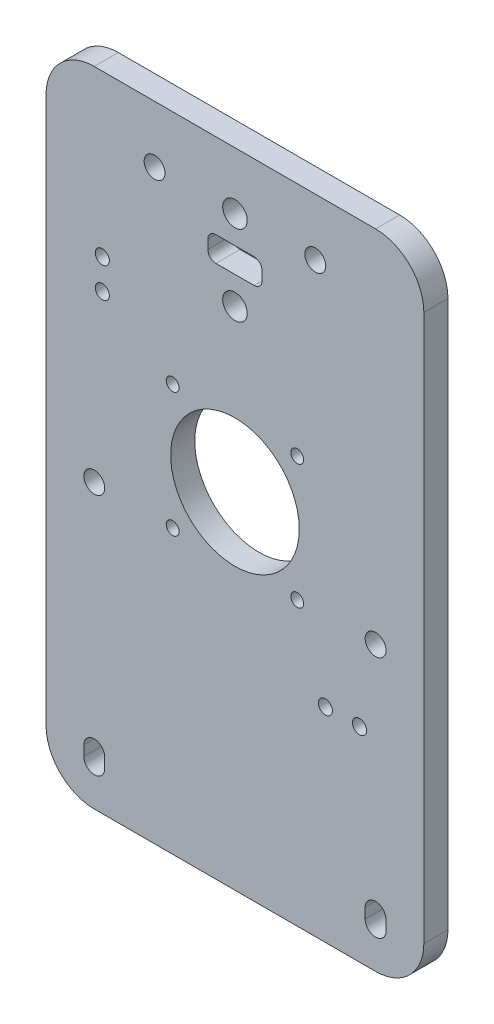
SolidWorks part; units mm, degrees
material "Acrylic (Medium-high impact)"
ref_plane "Спереди" through (0, 0, 0) normal (0, 0, 1) x (1, 0, 0)
ref_plane "Сверху" through (0, 0, 0) normal (0, 1, 0) x (1, 0, 0)
ref_plane "Справа" through (0, 0, 0) normal (1, 0, 0) x (0, 0, -1)
sketch "Model" plane through (0, 0, 0) normal (0, 0, 1) x (1, 0, 0)
  line L0 (-2.3021, 85.8) -> (5.2264, 85.8) construction
  line L1 (6.75, 135.8) -> (-6.75, 135.8) construction
  line L5 (0, 27.6115) -> (0, 21.6925) construction
  line L7 (-15.5, 9.9369) -> (-15.5, 9.0934) construction
  line L8 (15.5, 9.9369) -> (15.5, 9.0934) construction
  line L24 (-35, 37.2847) -> (-35, 77.3985) construction
  line L25 (-31.4983, 12.5) -> (-38.4, 12.5) construction
  line L26 (-31.4983, 10) -> (-38.4, 10) construction
  line L27 (-35, 12.5) -> (-35, 10) construction
  line L28 (-32.4, 12.5) -> (-32.4, 10)
  line L29 (-37.6, 12.5) -> (-37.6, 10)
  line L40 (31.4983, 10) -> (38.4, 10) construction
  line L41 (31.4983, 12.5) -> (38.4, 12.5) construction
  line L42 (35, 37.2847) -> (35, 77.3985) construction
  line L43 (35, 12.5) -> (35, 10) construction
  line L44 (32.4, 12.5) -> (32.4, 10)
  line L45 (37.6, 12.5) -> (37.6, 10)
  line L47 (-26.0102, 145.8) -> (26.0946, 145.8) construction
  line L48 (0, 129.408) -> (0, 90.7064) construction
  line L51 (-38.85, 70.45) -> (-29.8907, 70.45) construction
  line L53 (-16.3166, 125.8) -> (17.7871, 125.8) construction
  line L58 (38.85, 70.45) -> (29.8907, 70.45) construction
  line L4875 (-35, 160) -> (35, 160)
  line L4882 (47, 148) -> (47, 12)
  line L4889 (35, 0) -> (-35, 0)
  line L4896 (-47, 12) -> (-47, 148)
  line L5609 (6.75, 138.9) -> (-6.75, 138.9)
  line L5610 (-6.75, 138.9) -> (-6.75, 132.7)
  line L5611 (-6.75, 132.7) -> (6.75, 132.7)
  line L5612 (6.75, 132.7) -> (6.75, 138.9)
  line L6648 (-6.75, 138.9) -> (6.75, 138.9)
  line L6649 (6.75, 138.9) -> (6.75, 132.7)
  line L6650 (6.75, 132.7) -> (-6.75, 132.7)
  line L6651 (-6.75, 132.7) -> (-6.75, 138.9)
  arc A0 (-47, 12) -> (-35, 0) centre (-35, 12) ccw
  arc A1 (35, 0) -> (47, 12) centre (35, 12) ccw
  arc A2 (47, 148) -> (35, 160) centre (35, 148) ccw
  arc A3 (-35, 160) -> (-47, 148) centre (-35, 148) ccw
  circle A4 centre (0, 85.8) radius 16
  arc A13 (-32.4, 12.5) -> (-37.6, 12.5) centre (-35, 12.5) ccw
  arc A14 (-37.6, 10) -> (-32.4, 10) centre (-35, 10) ccw
  arc A19 (32.4, 12.5) -> (37.6, 12.5) centre (35, 12.5) cw
  arc A20 (37.6, 10) -> (32.4, 10) centre (35, 10) cw
  circle A29 centre (0, 145.8) radius 3.05
  circle A30 centre (-20, 145.8) radius 2.6
  circle A31 centre (20, 145.8) radius 2.6
  circle A32 centre (-35, 70.45) radius 2.6
  circle A33 centre (0, 125.8) radius 3.05
  circle A36 centre (35, 70.45) radius 2.6
  point P17 (0, 0)
  point P77 (-35, 11.25)
  point P114 (35, 11.25)
  point P127 (0, 160)
  dimension "D5" = 32
  dimension "D30" = 5.2
  dimension "D33" = 5.2
  dimension "D35" = 6.1
  dimension "D2" = 70
  dimension "D3" = 160
  dimension "D6" = 15.5
  dimension "D15" = 12
  dimension "D16" = 2.5
  dimension "D17" = 10
  dimension "D18" = 5.2
  dimension "D25" = 14.2
  dimension "D34" = 20
  dimension "D41" = 13.5
  dimension "D42" = 6.2
  dimension "D9" = 70
  dimension "D10" = 57.95
  dimension "D12" = 20
  dimension "D13" = 20
  dimension "D11" = 10
  dimension "D7" = 74.2
extrude "Base" add sketch "Model" along normal blind 6
sketch "Sketch1" plane through (0, 0, 6) normal (0, 0, 1) x (1, 0, 0)
  line L1 (-35, 160) -> (35, 160) construction
  line L2 (-47, 12) -> (-47, 148) construction
  circle A0 centre (-33, 120) radius 1.75
  circle A1 centre (-33, 112.5) radius 1.75
  dimension "D1" = 3.5
  dimension "D3" = 7.5
  dimension "D4" = 14
  dimension "D5" = 40
extrude "SensorMount" cut sketch "Sketch1" against normal through all contours A1 | A0
sketch "Sketch2" plane through (0, 0, 6) normal (0, 0, 1) x (1, 0, 0)
  line L0 (35, 0) -> (-35, 0) construction
  line L1 (-47, 12) -> (-47, 148) construction
  circle A0 centre (22.5, 50.76) radius 1.75
  circle A1 centre (31, 50.76) radius 1.75
  dimension "D1" = 3.5
  dimension "D3" = 8.5
  dimension "D4" = 50.76
  dimension "D5" = 69.5
extrude "CableMount" cut sketch "Sketch2" against normal blind 10 contours A0 | A1
fillet "FilletCableSlot" radius 2 4 edges at (6.75, 138.9, 3) (-6.75, 138.9, 3) (-6.75, 132.7, 3) (6.75, 132.7, 3)
hole_wizard "Ø3.2 (3.2) Stepper mount Holes" positions "Sketch6" profile "Sketch7" hole size "Ø3.2" standard "ANSI Metric" end condition through all
sketch "Sketch6" plane through (0, 0, 6) normal (0, 0, 1) x (1, 0, 0)
  line L0 (-50.1491, 85.8) -> (50.1491, 85.8) construction
  line L2 (0, 0) -> (0, 95.4376) construction
  line L3 (35, 0) -> (-35, 0) construction
  circle A0 centre (0, 85.8) radius 16 construction
  point P0 (-15.5, 101.3)
  point P3 (-15.5, 70.3)
  point P6 (15.5, 70.3)
  point P9 (15.5, 101.3)
  point P22 (0, 85.8)
  dimension "D1" = 31
  dimension "D2" = 31
sketch "Sketch7" plane through (-15.5, 101.3, 6) normal (1, 0, 0) x (0, -1, 0)
  line L0 (0, 0) -> (0, 6)
  line L1 (0, 6) -> (1.6, 6)
  line L2 (1.6, 6) -> (1.6, 0)
  line L5 (1.6, 0) -> (0, 0)
  line L11 (0, -6.35) -> (0, 107.95) construction
  dimension "Thru Hole Dia." = 3.2
  dimension "Thru Hole Depth" = 6
equation "\"D11@Model\"=\"D34@Model\"/2"
